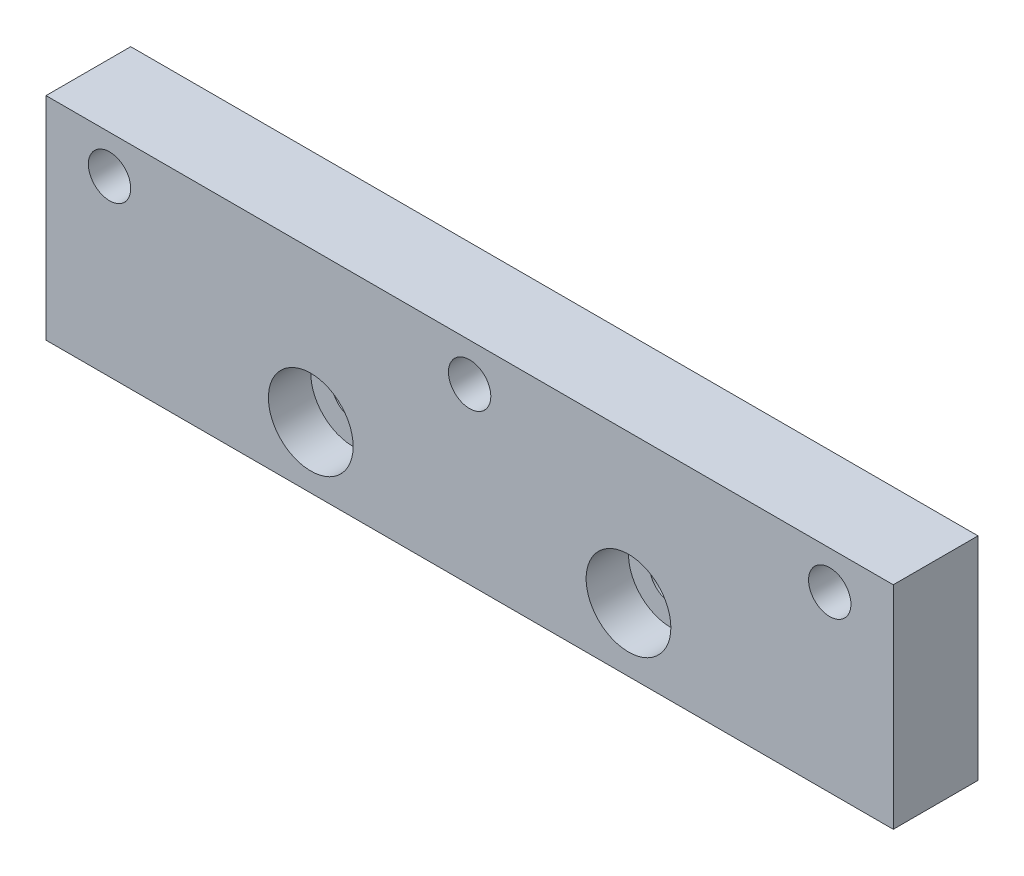
SolidWorks part; units mm, degrees
ref_plane "Front Plane" through (0, 0, 0) normal (0, 0, 1) x (1, 0, 0)
ref_plane "Top Plane" through (0, 0, 0) normal (0, 1, 0) x (1, 0, 0)
ref_plane "Right Plane" through (0, 0, 0) normal (1, 0, 0) x (0, 0, -1)
sketch "Sketch2" plane through (0, 0, 0) normal (0, 0, 1) x (1, 0, 0)
  line L1 (-20, 5) -> (20, 5)
  line L2 (-20, 5) -> (-20, -5)
  line L3 (-20, -5) -> (20, -5)
  line L4 (20, 5) -> (20, -5)
  line L5 (-20, 5) -> (20, -5) construction
  line L6 (-20, -5) -> (20, 5) construction
  point P0 (0, 0)
  dimension "D1" = 10
  dimension "D2" = 40
extrude "Boss-Extrude1" add sketch "Sketch2" along normal blind 4
sketch "Sketch3" plane through (0, 0, 4) normal (0, 0, 1) x (1, 0, 0)
  line L1 (0, 5) -> (0, -5) construction
  line L2 (20, 5) -> (-20, 5) construction
  line L3 (-20, -5) -> (20, -5) construction
  line L4 (-7.5, -2) -> (7.5, -2) construction
  circle A0 centre (-17, 3.2) radius 1
  circle A1 centre (0, 3.2) radius 1
  circle A2 centre (17, 3.2) radius 1
  circle A3 centre (-7.5, -2) radius 1
  circle A4 centre (7.5, -2) radius 1
  point P9 (-10.9049, -2.1097)
  point P18 (7.8515, -2.9291)
  point P19 (0, -2)
  point P20 (-7.5, -2)
  point P21 (0, 0)
  dimension "D1" = 2
  dimension "D2" = 2
  dimension "D3" = 2
  dimension "D6" = 2
  dimension "D7" = 2
  dimension "D4" = 17
  dimension "D5" = 17
  dimension "D8" = 15
  dimension "D9" = 3
extrude "Cut-Extrude1" cut sketch "Sketch3" against normal through all
sketch "Sketch4" plane through (0, 0, 4) normal (0, 0, 1) x (1, 0, 0)
  circle A0 centre (-7.5, -2.1) radius 2
  circle A1 centre (7.5, -2) radius 2
  dimension "D1" = 4
  dimension "D2" = 4
extrude "Cut-Extrude2" cut sketch "Sketch4" against normal blind 2
